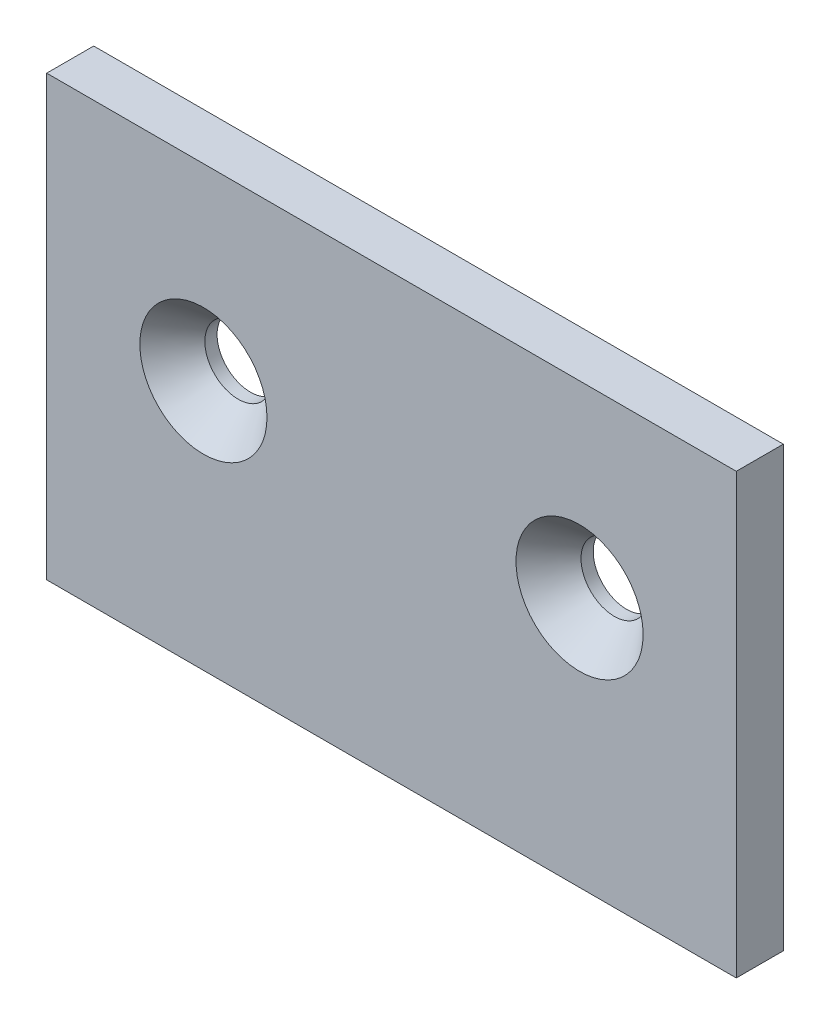
SolidWorks part; units mm, degrees
material "AISI 1045 Acero estirado en frío"
ref_plane "Alzado" through (0, 0, 0) normal (0, 0, 1) x (1, 0, 0)
ref_plane "Planta" through (0, 0, 0) normal (0, 1, 0) x (1, 0, 0)
ref_plane "Vista lateral" through (0, 0, 0) normal (1, 0, 0) x (0, 0, -1)
sketch "Croquis1" plane through (0, 0, 0) normal (0, 0, 1) x (1, 0, 0)
  line L1 (0, 0) -> (69.85, 0)
  line L2 (0, 0) -> (0, 44.45)
  line L3 (0, 44.45) -> (69.85, 44.45)
  line L4 (69.85, 0) -> (69.85, 44.45)
  dimension "D1" = 69.85
  dimension "D2" = 44.45
extrude "Saliente-Extruir1" add sketch "Croquis1" along normal blind 4.7625
hole_wizard "Avellanado para tornillo con cabeza ovalada de 1/41" positions "Croquis2" profile "Croquis3" countersink size "1/4" standard "Ansi Inch" end condition through all
sketch "Croquis2" plane through (0, 0, 4.7625) normal (0, 0, 1) x (1, 0, 0)
  line L0 (0, 25.4) -> (69.85, 25.4) construction
  line L1 (0, 44.45) -> (0, 0) construction
  line L2 (69.85, 0) -> (69.85, 44.45) construction
  line L4 (0, 0) -> (69.85, 0) construction
  point P11 (15.875, 25.4)
  point P13 (53.975, 25.4)
  dimension "D1" = 25.4
  dimension "D2" = 38.1
  dimension "D3" = 15.875
sketch "Croquis3" plane through (53.975, 25.4, 4.7625) normal (1, 0, 0) x (0, -1, 0)
  line L0 (0, 0) -> (0, 4.7625)
  line L1 (0, 4.7625) -> (3.3782, 4.7625)
  line L2 (3.3782, 4.7625) -> (3.3782, 3.5209)
  line L3 (3.3782, 3.5209) -> (6.4389, 0)
  line L5 (6.4389, 0) -> (0, 0)
  line L6 (-3.3782, 3.5209) -> (-6.4389, 0) construction
  line L11 (0, -6.35) -> (0, 107.95) construction
  dimension "Diámetro de taladro hasta el siguiente" = 6.7564
  dimension "Profundidad de taladro hasta el siguiente" = 4.7625
  dimension "Diámetro de avellanado cercano" = 12.8778
  dimension "Ángulo de avellanado cercano" = 82
